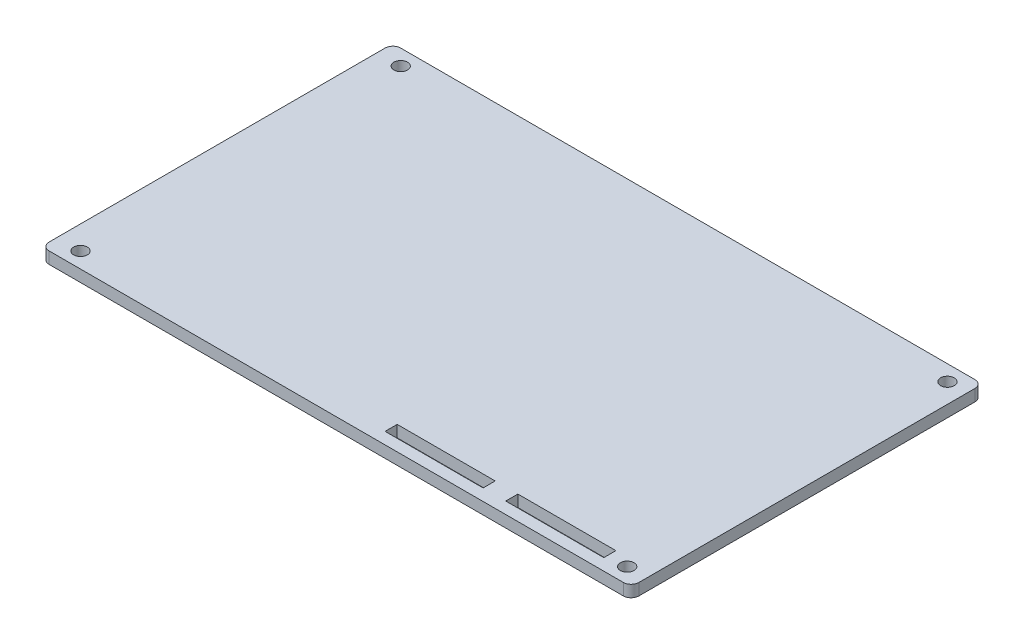
SolidWorks part; units mm, degrees
ref_plane "Front Plane" through (0, 0, 0) normal (0, 0, 1) x (1, 0, 0)
ref_plane "Top Plane" through (0, 0, 0) normal (0, 1, 0) x (1, 0, 0)
ref_plane "Right Plane" through (0, 0, 0) normal (1, 0, 0) x (0, 0, -1)
sketch "Sketch1" plane through (0, 0, 0) normal (0, 1, 0) x (1, 0, 0)
  line L1 (0, 0) -> (151, 0)
  line L2 (0, 0) -> (0, 90)
  line L3 (0, 90) -> (151, 90)
  line L4 (151, 0) -> (151, 90)
  dimension "D1" = 151
  dimension "D2" = 90
extrude "Boss-Extrude1" add sketch "Sketch1" along normal blind 3
sketch "Sketch2" plane through (0, 3, 0) normal (0, 1, 0) x (1, 0, 0)
  line L0 (151, 0) -> (151, 90) construction
  line L1 (151, 90) -> (0, 90) construction
  line L2 (0, 0) -> (151, 0) construction
  line L3 (0, 90) -> (0, 0) construction
  circle A0 centre (146, 86) radius 1.75
  circle A1 centre (146, 4) radius 1.75
  circle A2 centre (6, 86) radius 1.75
  circle A3 centre (6, 4) radius 1.75
  dimension "D1" = 3.5
  dimension "D2" = 5
  dimension "D3" = 4
  dimension "D4" = 3.5
  dimension "D5" = 5
  dimension "D6" = 4
  dimension "D7" = 4
  dimension "D8" = 6
  dimension "D9" = 3.5
  dimension "D10" = 3.5
  dimension "D11" = 6
  dimension "D12" = 4
extrude "Cut-Extrude1" cut sketch "Sketch2" against normal through all
fillet "Fillet1" radius 2 4 edges at (151, 1.5, -90) (151, 1.5, 0) (0, 1.5, 0) (0, 1.5, -90)
sketch "Sketch3" plane through (0, 3, 0) normal (0, 1, 0) x (1, 0, 0)
  line L0 (141, 3) -> (85, 3) construction
  line L1 (151, 2) -> (151, 88) construction
  line L2 (2, 0) -> (149, 0) construction
  line L4 (85, 3) -> (110.1, 3)
  line L5 (85, 3) -> (85, 6.1)
  line L6 (85, 6.1) -> (110.1, 6.1)
  line L7 (110.1, 3) -> (110.1, 6.1)
  line L8 (141, 3) -> (115.9, 3)
  line L9 (141, 3) -> (141, 6.1)
  line L10 (141, 6.1) -> (115.9, 6.1)
  line L11 (115.9, 3) -> (115.9, 6.1)
  dimension "D1" = 56
  dimension "D2" = 10
  dimension "D3" = 3
  dimension "D4" = 3.1
  dimension "D5" = 25.1
  dimension "D6" = 3.1
  dimension "D7" = 25.1
extrude "Cut-Extrude2" cut sketch "Sketch3" against normal through all
